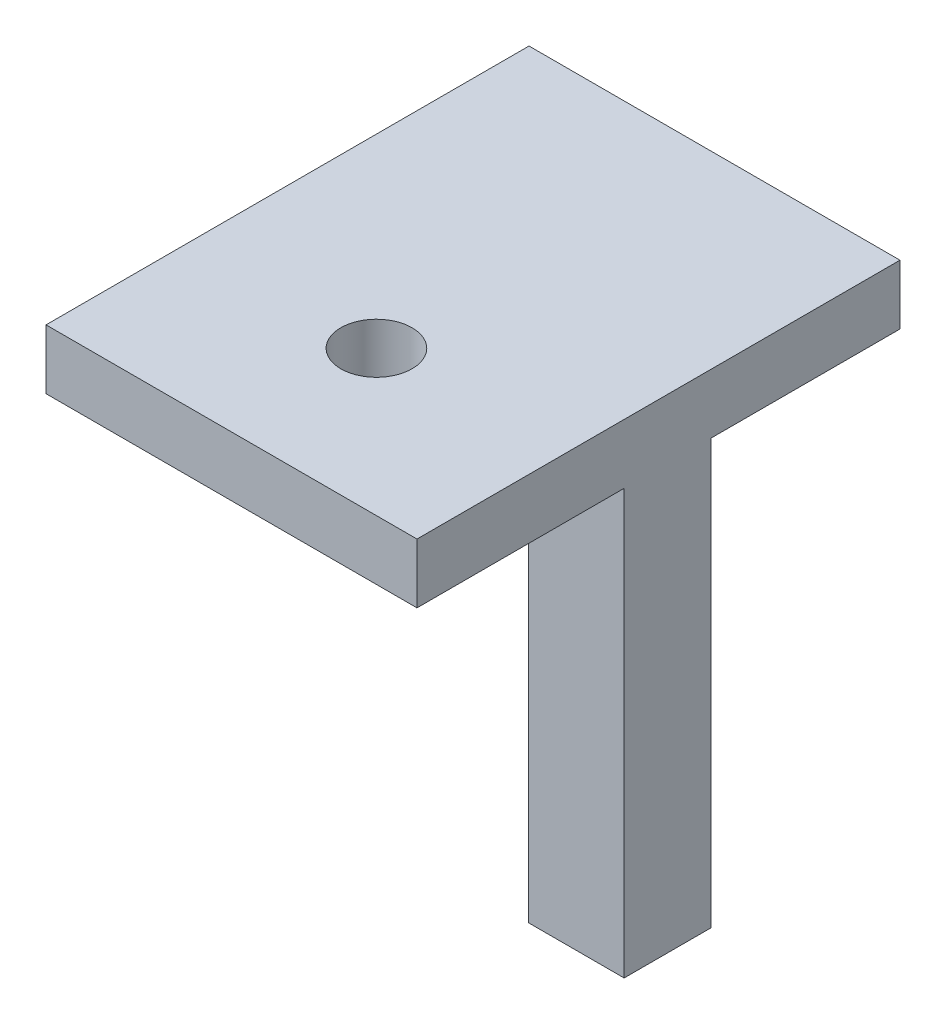
SolidWorks part; units mm, degrees
ref_plane "Front Plane" through (0, 0, 0) normal (0, 0, 1) x (1, 0, 0)
ref_plane "Top Plane" through (0, 0, 0) normal (0, 1, 0) x (1, 0, 0)
ref_plane "Right Plane" through (0, 0, 0) normal (1, 0, 0) x (0, 0, -1)
sketch "Sketch1" plane through (0, 0, 0) normal (0, 1, 0) x (1, 0, 0)
  line L1 (-31.1, 40.4921) -> (31.1, 40.4921)
  line L2 (-31.1, 40.4921) -> (-31.1, -40.4921)
  line L3 (-31.1, -40.4921) -> (31.1, -40.4921)
  line L4 (31.1, 40.4921) -> (31.1, -40.4921)
  line L5 (-31.1, 40.4921) -> (31.1, -40.4921) construction
  line L6 (-31.1, -40.4921) -> (31.1, 40.4921) construction
  point P0 (0, 0)
  dimension "D1" = 62.2
  dimension "D2" = 80.9841
extrude "Boss-Extrude1" add sketch "Sketch1" along normal blind 10
sketch "Sketch2" plane through (0, 10, 0) normal (0, 1, 0) x (1, 0, 0)
  line L0 (-31.1, -40.4921) -> (31.1, -40.4921) construction
  circle A0 centre (0, -16.1921) radius 5.969
  dimension "D1" = 24.3
extrude "Cut-Extrude1" cut sketch "Sketch2" against normal blind 10
sketch "Sketch3" plane through (0, 0, 0) normal (0, -1, 0) x (1, 0, 0)
  line L0 (31.1, -40.4921) -> (-31.1, -40.4921) construction
  line L1 (31.1, -8.7921) -> (15.1, -8.7921)
  line L2 (31.1, -8.7921) -> (31.1, 5.7606)
  line L3 (31.1, 5.7606) -> (15.1, 5.7606)
  line L4 (15.1, -8.7921) -> (15.1, 5.7606)
  line L7 (31.1, 40.4921) -> (31.1, -40.4921) construction
  dimension "D1" = 16
  dimension "D2" = 31.7
  dimension "D3" = 14.5526
  dimension "D4" = 0
extrude "Boss-Extrude2" add sketch "Sketch3" along normal blind 71.11
